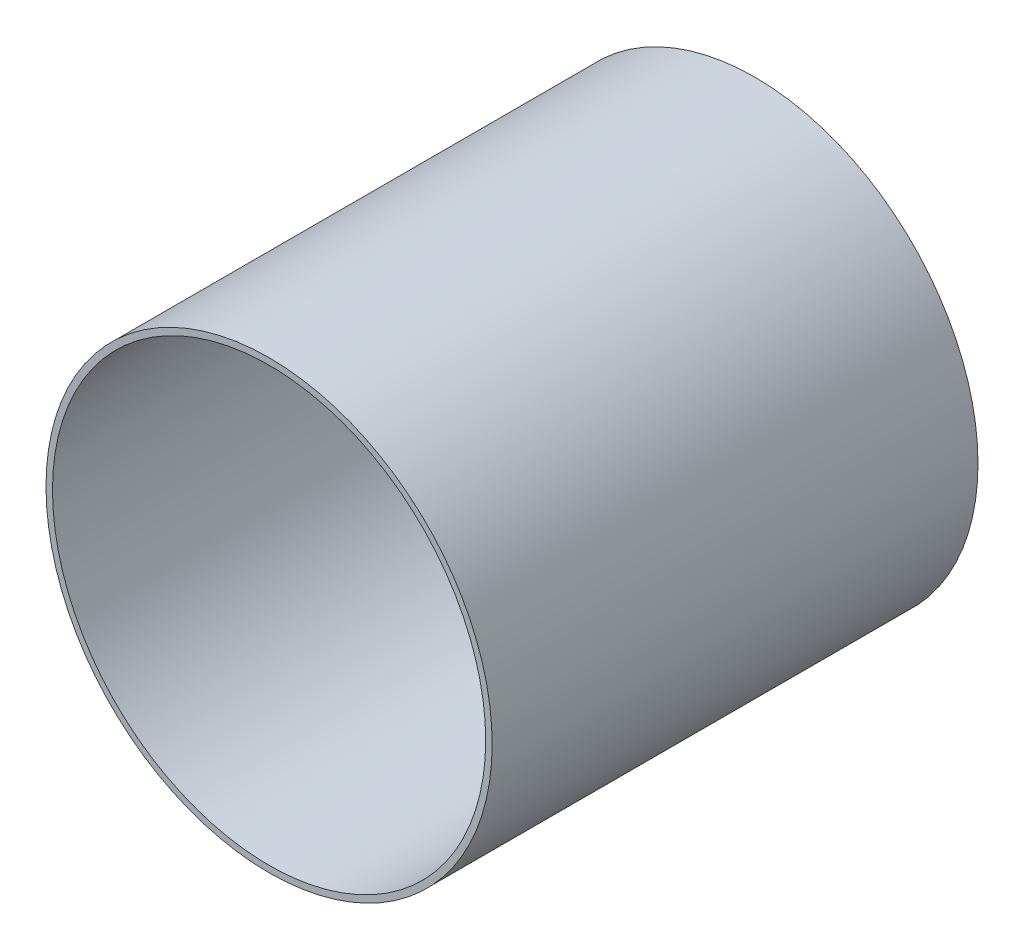
SolidWorks part; units mm, degrees
ref_plane "Ebene vorne" through (0, 0, 0) normal (0, 0, 1) x (1, 0, 0)
ref_plane "Ebene oben" through (0, 0, 0) normal (0, 1, 0) x (1, 0, 0)
ref_plane "Ebene rechts" through (0, 0, 0) normal (1, 0, 0) x (0, 0, -1)
sketch "Skizze1" plane through (0, 0, 0) normal (0, 0, 1) x (1, 0, 0)
  circle A0 centre (0, 0) radius 26.75
  circle A1 centre (0, 0) radius 27.55
  dimension "D1" = 53.5
  dimension "D2" = 0.8
extrude "Aufsatz-Linear austragen1" add sketch "Skizze1" along normal blind 60
